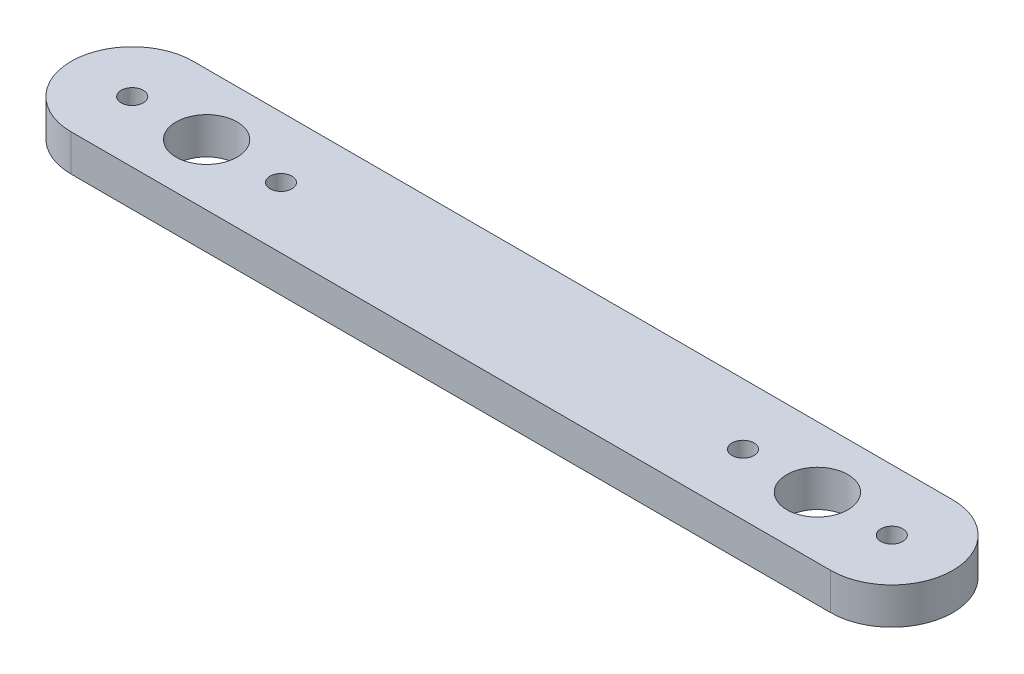
SolidWorks part; units mm, degrees
ref_plane "Alzado" through (0, 0, 0) normal (0, 0, 1) x (1, 0, 0)
ref_plane "Planta" through (0, 0, 0) normal (0, 1, 0) x (1, 0, 0)
ref_plane "Vista lateral" through (0, 0, 0) normal (1, 0, 0) x (0, 0, -1)
sketch "Croquis1" plane through (0, 0, 0) normal (0, 1, 0) x (1, 0, 0)
  line L0 (-25, 0) -> (25, 0) construction
  line L1 (-25, 0) -> (-31.09, 0) construction
  line L2 (25, 0) -> (31.09, 0) construction
  line L3 (-31.09, 5) -> (31.09, 5)
  line L4 (-31.09, -5) -> (31.09, -5)
  circle A0 centre (-25, 0) radius 2.5
  circle A1 centre (25, 0) radius 2.5
  circle A2 centre (-18.91, 0) radius 0.9
  circle A3 centre (18.91, 0) radius 0.9
  circle A4 centre (-31.09, 0) radius 0.9
  circle A5 centre (31.09, 0) radius 0.9
  arc A6 (-31.09, 5) -> (-31.09, -5) centre (-31.09, 0) ccw
  arc A8 (31.09, -5) -> (31.09, 5) centre (31.09, 0) ccw
  dimension "D3" = 5
  dimension "D4" = 5
  dimension "D9" = 10
  dimension "D11" = 1.8
  dimension "D12" = 1.8
  dimension "D13" = 1.8
  dimension "D14" = 1.8
  dimension "D1" = 50
  dimension "D2" = 25
  dimension "D5" = 6.09
  dimension "D6" = 6.09
  dimension "D7" = 6.09
  dimension "D8" = 6.09
extrude "Saliente-Extruir1" add sketch "Croquis1" along normal blind 3
